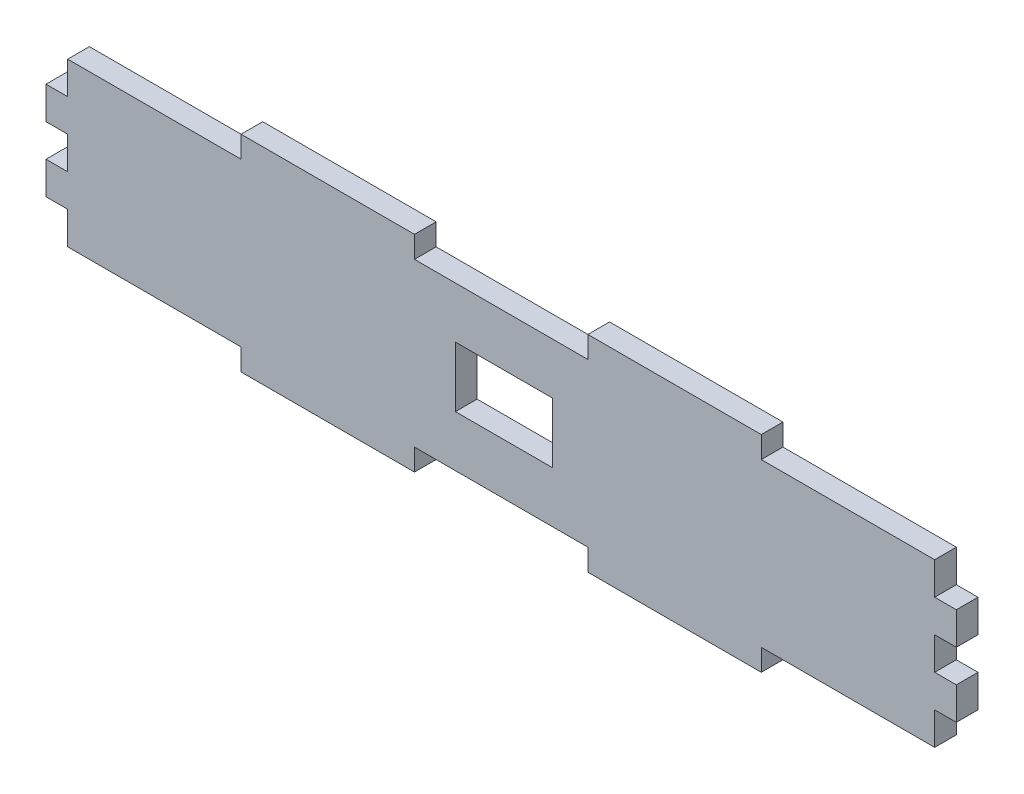
SolidWorks part; units mm, degrees
ref_plane "Front Plane" through (0, 0, 0) normal (0, 0, 1) x (1, 0, 0)
ref_plane "Top Plane" through (0, 0, 0) normal (0, 1, 0) x (1, 0, 0)
ref_plane "Right Plane" through (0, 0, 0) normal (1, 0, 0) x (0, 0, -1)
sketch "Sketch1" plane through (0, 0, 0) normal (0, 0, 1) x (1, 0, 0)
  line L2 (-69.4169, 21.7207) -> (-69.4169, 17.2207)
  line L4 (50.5831, 21.7207) -> (50.5831, 17.2207)
  line L6 (-45.4169, 24.7207) -> (-45.4169, 21.7207)
  line L9 (-45.4169, -3.7793) -> (-45.4169, -0.7793)
  line L10 (-21.4169, 21.7207) -> (-21.4169, 24.7207)
  line L12 (2.5831, 24.7207) -> (2.5831, 21.7207)
  line L13 (26.5831, 21.7207) -> (26.5831, 24.7207)
  line L14 (-15.7486, 14.6407) -> (-2.3286, 14.6407)
  line L16 (-21.4169, 21.7207) -> (-21.4169, 24.7207)
  line L17 (-15.7486, 14.6407) -> (-15.7486, 6.3007)
  line L18 (2.5831, 24.7207) -> (2.5831, 21.7207)
  line L19 (-21.4169, -0.7793) -> (-21.4169, -3.7793)
  line L20 (-15.7486, 6.3007) -> (-2.3286, 6.3007)
  line L21 (2.5831, -3.7793) -> (2.5831, -0.7793)
  line L22 (26.5831, 21.7207) -> (26.5831, 24.7207)
  line L23 (-2.3286, 14.6407) -> (-2.3286, 6.3007)
  line L25 (26.5831, -0.7793) -> (26.5831, -3.7793)
  line L30 (-69.4169, 17.2207) -> (-72.4169, 17.2207)
  line L31 (-72.4169, 17.2207) -> (-72.4169, 12.7207)
  line L32 (-72.4169, 12.7207) -> (-69.4169, 12.7207)
  line L33 (50.5831, 17.2207) -> (53.5831, 17.2207)
  line L34 (53.5831, 17.2207) -> (53.5831, 12.7207)
  line L35 (53.5831, 12.7207) -> (50.5831, 12.7207)
  line L36 (50.5831, 8.2207) -> (53.5831, 8.2207)
  line L37 (53.5831, 8.2207) -> (53.5831, 3.7207)
  line L38 (53.5831, 3.7207) -> (50.5831, 3.7207)
  line L39 (50.5831, 8.2207) -> (53.5831, 8.2207)
  line L40 (53.5831, 8.2207) -> (53.5831, 3.7207)
  line L41 (53.5831, 3.7207) -> (50.5831, 3.7207)
  line L42 (-69.4169, 8.2207) -> (-72.4169, 8.2207)
  line L43 (-72.4169, 8.2207) -> (-72.4169, 3.7207)
  line L44 (-72.4169, 3.7207) -> (-69.4169, 3.7207)
  line L45 (-69.4169, 12.7207) -> (-69.4169, 8.2207)
  line L46 (-69.4169, 3.7207) -> (-69.4169, -0.7793)
  line L47 (50.5831, 12.7207) -> (50.5831, 8.2207)
  line L48 (50.5831, 3.7207) -> (50.5831, -0.7793)
  line L49 (-45.4169, -3.7793) -> (-21.4169, -3.7793)
  line L50 (2.5831, -3.7793) -> (26.5831, -3.7793)
  line L51 (26.5831, 24.7207) -> (2.5831, 24.7207)
  line L52 (-21.4169, 24.7207) -> (-45.4169, 24.7207)
  line L53 (-69.4169, -0.7793) -> (-45.4169, -0.7793)
  line L54 (-45.4169, 21.7207) -> (-69.4169, 21.7207)
  line L55 (-21.4169, 21.7207) -> (2.5831, 21.7207)
  line L56 (-21.4169, -0.7793) -> (2.5831, -0.7793)
  line L57 (26.5831, 21.7207) -> (50.5831, 21.7207)
  line L58 (26.5831, -0.7793) -> (50.5831, -0.7793)
  line L60 (50.5831, 24.7207) -> (50.5831, 21.7207) [skipped]
  line L61 (50.5831, 24.7207) -> (50.5831, 21.7207) [skipped]
  line L62 (50.5831, -3.7793) -> (50.5831, -0.7793) [skipped]
  dimension "D1" = 120
  dimension "D2" = 22.5
  dimension "D3" = 24
  dimension "D4" = 13.42
  dimension "D5" = 8.34
  dimension "D6" = 7.08
  dimension "D9" = 3
  dimension "D10" = 4.5
  dimension "D11" = 4.5
  dimension "D12" = 4.5
  dimension "D13" = 3
  dimension "D14" = 4.5
  dimension "D7" = 3
  dimension "D8" = 3
  dimension "D15" = 2
  dimension "D16" = 2
extrude "Boss-Extrude1" add sketch "Sketch1" along normal blind 3
